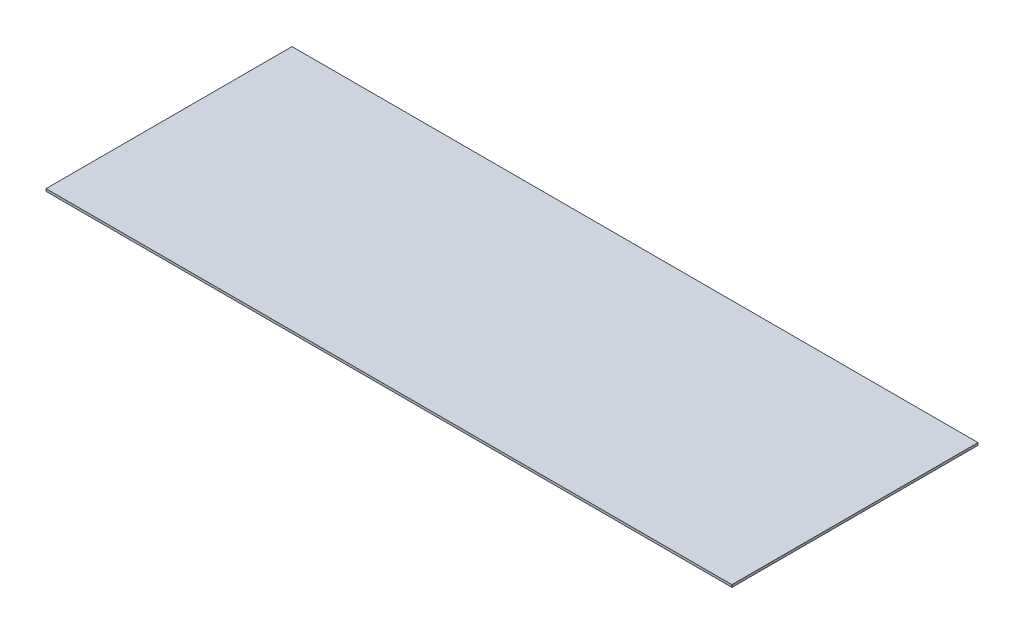
SolidWorks part; units mm, degrees
material "PET"
ref_plane "Front Plane" through (0, 0, 0) normal (0, 0, 1) x (1, 0, 0)
ref_plane "Top Plane" through (0, 0, 0) normal (0, 1, 0) x (1, 0, 0)
ref_plane "Right Plane" through (0, 0, 0) normal (1, 0, 0) x (0, 0, -1)
sketch "Sketch1" plane through (0, 0, 0) normal (0, 1, 0) x (1, 0, 0)
  line L1 (-28.575, 10.25) -> (28.575, 10.25)
  line L2 (-28.575, 10.25) -> (-28.575, -10.25)
  line L3 (-28.575, -10.25) -> (28.575, -10.25)
  line L4 (28.575, 10.25) -> (28.575, -10.25)
  line L5 (-28.575, 10.25) -> (28.575, -10.25) construction
  line L6 (-28.575, -10.25) -> (28.575, 10.25) construction
  point P0 (0, 0)
  dimension "D1" = 20.5
  dimension "D2" = 57.15
extrude "Boss-Extrude1" add sketch "Sketch1" along normal blind 0.2
